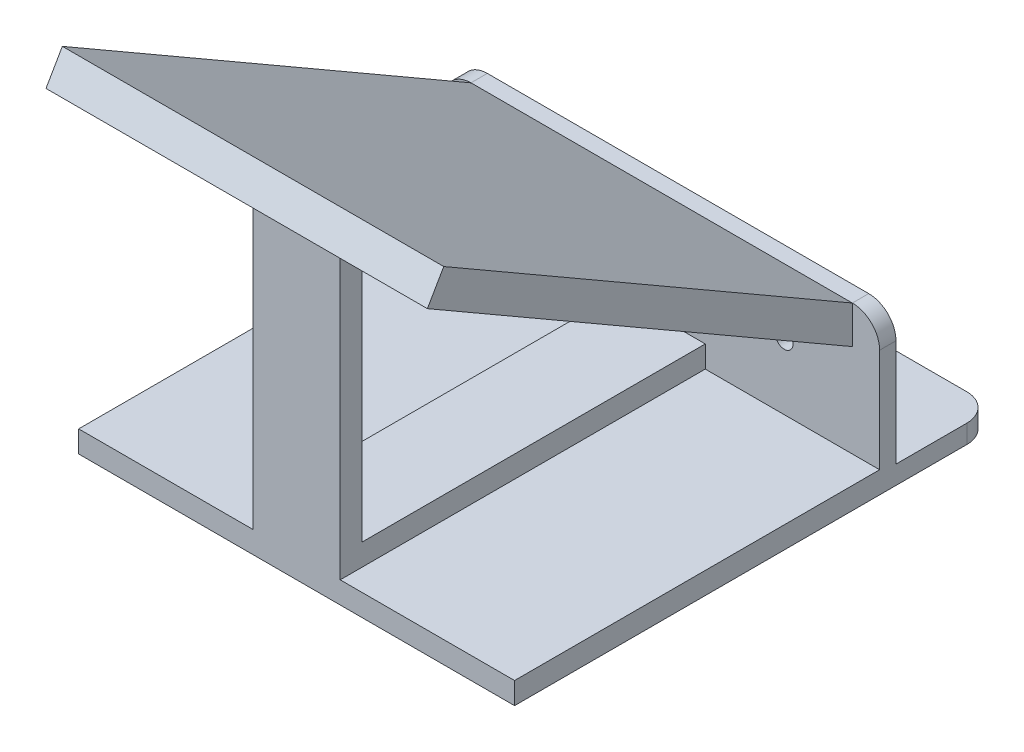
SolidWorks part; units mm, degrees
ref_plane "前视基准面" through (0, 0, 0) normal (0, 0, 1) x (1, 0, 0)
ref_plane "上视基准面" through (0, 0, 0) normal (0, 1, 0) x (1, 0, 0)
ref_plane "右视基准面" through (0, 0, 0) normal (1, 0, 0) x (0, 0, -1)
sketch "草图1" plane through (0, 0, 0) normal (0, 0, 1) x (1, 0, 0)
  line L0 (-40, 0) -> (40, 0) construction
  line L1 (-40, 12) -> (40, 12)
  line L2 (-40, 12) -> (-40, -12)
  line L3 (-40, -12) -> (40, -12)
  line L4 (40, 12) -> (40, -12)
  line L5 (-40, 12) -> (40, -12) construction
  line L6 (-40, -12) -> (40, 12) construction
  line L7 (0, 12) -> (0, -12) construction
  circle A0 centre (-22.5, 0) radius 1.6
  circle A1 centre (22.5, 0) radius 1.6
  point P0 (0, 0)
  dimension "D3" = 3.2
  dimension "D4" = 22.5
  dimension "D1" = 24
  dimension "D2" = 80
extrude "凸台-拉伸1" add sketch "草图1" along normal blind 3
sketch "草图2" plane through (0, -12, 0) normal (0, -1, 0) x (1, 0, 0)
  line L0 (40, 3) -> (40, 0) construction
  line L1 (-40, 0) -> (40, 0)
  line L2 (-40, 0) -> (-40, 70)
  line L3 (-40, 70) -> (40, 70)
  line L4 (40, 0) -> (40, 70)
  dimension "D1" = 0
  dimension "D2" = 70
extrude "凸台-拉伸2" add sketch "草图2" along normal blind 4
sketch "草图3" plane through (0, -16, 0) normal (0, -1, 0) x (1, 0, 0)
  line L1 (-40, 0) -> (40, 0)
  line L2 (-40, 0) -> (-40, -18)
  line L3 (-40, -18) -> (40, -18)
  line L4 (40, 0) -> (40, -18)
  dimension "D1" = 80
  dimension "D2" = 18
extrude "凸台-拉伸3" add sketch "草图3" against normal blind 4
sketch "草图4" plane through (0, -12, 0) normal (0, 1, 0) x (1, 0, 0)
  line L1 (-40, 18) -> (40, 18)
  line L2 (-40, 18) -> (-40, 0)
  line L3 (-40, 0) -> (40, 0)
  line L4 (40, 18) -> (40, 0)
extrude "切除-拉伸1" cut sketch "草图4" against normal blind 0.6
fillet "圆角1" radius 5 2 edges at (-40, -14.3, -18) (40, -14.3, -18)
fillet "圆角2" radius 5 2 edges at (-40, 12, 1.5) (40, 12, 1.5)
sketch "草图5" plane through (0, -12, 0) normal (0, 1, 0) x (1, 0, 0)
  line L0 (0, 0) -> (0, -70) construction
  line L1 (40, -70) -> (-40, -70) construction
  line L2 (-40, -3) -> (40, -3) construction
  line L3 (-8, -70) -> (8, -70)
  line L4 (-8, -70) -> (-8, -3)
  line L5 (-8, -3) -> (8, -3)
  line L6 (8, -70) -> (8, -3)
  dimension "D1" = 8
  dimension "D2" = 8
extrude "凸台-拉伸4" add sketch "草图5" along normal blind 4
sketch "草图6" plane through (0, 0, 70) normal (0, 0, 1) x (1, 0, 0)
  line L0 (8, -8) -> (8, -12) construction
  line L1 (-8, -8) -> (8, -8)
  line L2 (-8, -8) -> (-8, 32)
  line L3 (-8, 32) -> (8, 32)
  line L4 (8, -8) -> (8, 32)
  dimension "D1" = 0
  dimension "D2" = 40
extrude "凸台-拉伸5" add sketch "草图6" against normal blind 4
ref_plane "基准面1" through (0, 0, 0) normal (-1, 0, 0) x (0, 0, 1)
sketch "草图8" plane through (0, 0, 0) normal (-1, 0, 0) x (0, 0, 1)
  line L0 (3, 12) -> (78, 55.3013)
  line L3 (78, 12) -> (3, 12) construction
  line L4 (3, 5.0718) -> (78, 48.3731)
  line L5 (3, 7) -> (3, 12) construction
  line L6 (3, 5.0718) -> (3, 12)
  line L7 (78, 12) -> (78, 48.3731) construction
  line L9 (78, 55.3013) -> (78, 48.3731)
  line L11 (70, 32) -> (70, -12) construction
  dimension "D1" = 30
  dimension "D2" = 6
  dimension "D3" = 60
  dimension "D4" = 75
  dimension "D5" = 0
extrude "凸台-拉伸6" add sketch "草图8" along normal blind 35 and the other way blind 35
sketch "草图9" plane through (0, 0, 66) normal (0, 0, -1) x (-1, 0, 0)
  line L6 (-8, -8) -> (-8, 32) construction
  line L7 (8, 32) -> (-8, 32)
  line L8 (8, 32) -> (8, 47)
  line L9 (8, 47) -> (-8, 47)
  line L10 (-8, 32) -> (-8, 47)
  dimension "D1" = 0
  dimension "D2" = 15
extrude "凸台-拉伸7" add sketch "草图9" against normal blind 4
sketch "草图11" plane through (35, 0, 0) normal (1, 0, 0) x (0, 0, -1)
  line L0 (-78, 48.3731) -> (-81, 50.1051)
  line L1 (-81, 50.1051) -> (-78, 55.3013)
  line L2 (-78, 48.3731) -> (-78, 55.3013)
  line L3 (-3, 5.0718) -> (-78, 48.3731) construction
  dimension "D1" = 90
  dimension "D2" = 180
extrude "凸台-拉伸9" add sketch "草图11" against normal blind 70
